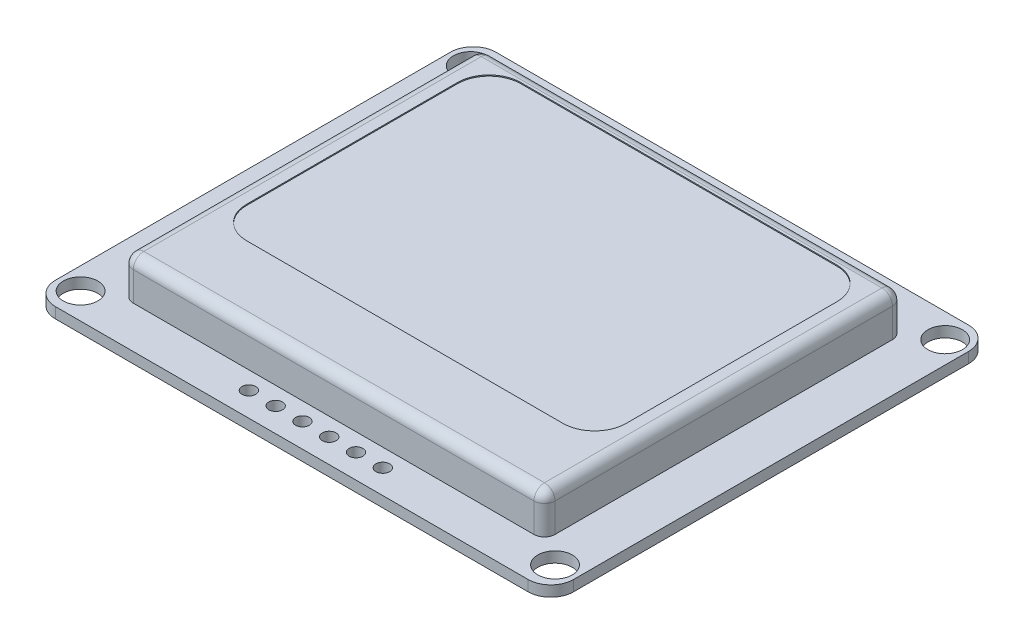
SolidWorks part; units mm, degrees
ref_plane "Front Plane" through (0, 0, 0) normal (0, 0, 1) x (1, 0, 0)
ref_plane "Top Plane" through (0, 0, 0) normal (0, 1, 0) x (1, 0, 0)
ref_plane "Right Plane" through (0, 0, 0) normal (1, 0, 0) x (0, 0, -1)
sketch "Sketch2" plane through (0, 0, 0) normal (0, 1, 0) x (1, 0, 0)
  line L0 (20, -17) -> (-20, 17) construction
  line L1 (-20, 17) -> (20, 17)
  line L2 (-20, 17) -> (-20, -17)
  line L3 (-20, -17) -> (20, -17)
  line L4 (20, 17) -> (20, -17)
  line L5 (0, -55) -> (0, 55) construction
  line L6 (-55, 0) -> (55, 0) construction
  point P4 (0, 0)
  dimension "D1" = 40
  dimension "D2" = 34
extrude "Boss-Extrude1" add sketch "Sketch2" along normal blind 3.75
sketch "Sketch3" plane through (0, 0, 0) normal (0, 1, 0) x (1, 0, 0)
  line L0 (-24.5745, -20.973) -> (24.5745, 20.81) construction
  line L1 (-24.5745, -20.973) -> (24.5745, -20.973)
  line L2 (-24.5745, -20.973) -> (-24.5745, 20.81)
  line L3 (-24.5745, 20.81) -> (24.5745, 20.81)
  line L4 (24.5745, -20.973) -> (24.5745, 20.81)
  line L5 (0, -2.0625) -> (0, 2.0625) construction
  line L7 (20, 17) -> (-20, 17) construction
  point P4 (0, -0.0815)
  dimension "D1" = 49.149
  dimension "D2" = 41.783
  dimension "D3" = 3.81
extrude "Boss-Extrude2" add sketch "Sketch3" against normal blind 1.016
sketch "Sketch4" plane through (0, 0, 0) normal (0, 1, 0) x (1, 0, 0)
  line L0 (-22.5, -988.3059) -> (-22.5, 49011.6941) construction
  line L1 (-1014.1743, 18.5) -> (48985.8257, 18.5) construction
  line L2 (-1019.6962, -18.5) -> (48980.3038, -18.5) construction
  line L3 (22.5, -985.7739) -> (22.5, 49014.2261) construction
  line L4 (-22.5, 18.5) -> (22.5, -18.5) construction
  line L5 (0, -2.6213) -> (0, 2.6213) construction
  line L6 (-2.6213, 0) -> (2.6213, 0) construction
  circle A0 centre (-22.5, 18.5) radius 1.6383
  circle A1 centre (-22.5, -18.5) radius 1.6383
  circle A2 centre (22.5, 18.5) radius 1.6383
  circle A3 centre (22.5, -18.5) radius 1.6383
  point P16 (0, 0)
  dimension "D1" = 3.2766
  dimension "D2" = 37
  dimension "D3" = 45
extrude "Cut-Extrude1" cut sketch "Sketch4" against normal up to next
fillet "Fillet1" radius 2.159 4 edges at (24.5745, -0.508, -20.81) (24.5745, -0.508, 20.973) (-24.5745, -0.508, 20.973) (-24.5745, -0.508, -20.81)
sketch "Sketch5" plane through (0, 0, 0) normal (0, 1, 0) x (1, 0, 0)
  line L0 (-1006.861, 19.2225) -> (48993.139, 19.2225) construction
  line L1 (0, -2.6213) -> (0, 2.6213) construction
  line L2 (-1016.8661, 0.2677) -> (48983.1339, 0.2677) construction
  line L4 (22.4155, 20.81) -> (-22.4155, 20.81) construction
  line L6 (-22.4155, -20.973) -> (22.4155, -20.973) construction
  circle A0 centre (-1.27, 19.2225) radius 0.6497
  circle A1 centre (-3.81, 19.2225) radius 0.6497
  circle A2 centre (-6.35, 19.2225) radius 0.6497
  circle A3 centre (1.27, 19.2225) radius 0.6497
  circle A4 centre (3.81, 19.2225) radius 0.6497
  circle A5 centre (6.35, 19.2225) radius 0.6497
  circle A6 centre (6.35, -18.687) radius 0.6497
  circle A7 centre (3.81, -18.687) radius 0.6497
  circle A8 centre (1.27, -18.687) radius 0.6497
  circle A9 centre (-6.35, -18.687) radius 0.6497
  circle A10 centre (-3.81, -18.687) radius 0.6497
  circle A11 centre (-1.27, -18.687) radius 0.6497
  dimension "D1" = 2.54
  dimension "D2" = 2.54
  dimension "D3" = 2.54
  dimension "D4" = 2.54
  dimension "D5" = 2.54
  dimension "D6" = 1.27
  dimension "D7" = 1.5875
  dimension "D8" = 2.286
extrude "Cut-Extrude2" cut sketch "Sketch5" against normal up to next
sketch "Sketch6" plane through (0, 3.75, 0) normal (0, 1, 0) x (1, 0, 0)
  line L0 (18, -10.25) -> (-18, 15.75) construction
  line L1 (-18, 15.75) -> (18, 15.75)
  line L2 (-18, 15.75) -> (-18, -10.25)
  line L3 (-18, -10.25) -> (18, -10.25)
  line L4 (18, 15.75) -> (18, -10.25)
  line L5 (0, -2.6213) -> (0, 2.6213) construction
  line L6 (-20, -17) -> (20, -17) construction
  point P4 (0, 2.75)
  dimension "D1" = 26
  dimension "D2" = 36
  dimension "D3" = 6.75
extrude "Cut-Extrude3" cut sketch "Sketch6" against normal blind 0.1016
fillet "Fillet2" radius 3 4 edges at (-18, 3.6992, 10.25) (18, 3.6992, 10.25) (18, 3.6992, -15.75) (-18, 3.6992, -15.75)
fillet "Fillet3" radius 1 4 edges at (-20, 1.875, -17) (-20, 1.875, 17) (20, 1.875, 17) (20, 1.875, -17)
fillet "Fillet4" radius 1 8 edges at (19.7071, 3.75, -16.7071) (20, 3.75, 0) (19.7071, 3.75, 16.7071) (0, 3.75, 17) (-19.7071, 3.75, 16.7071) (-20, 3.75, 0) (-19.7071, 3.75, -16.7071) (0, 3.75, -17)
